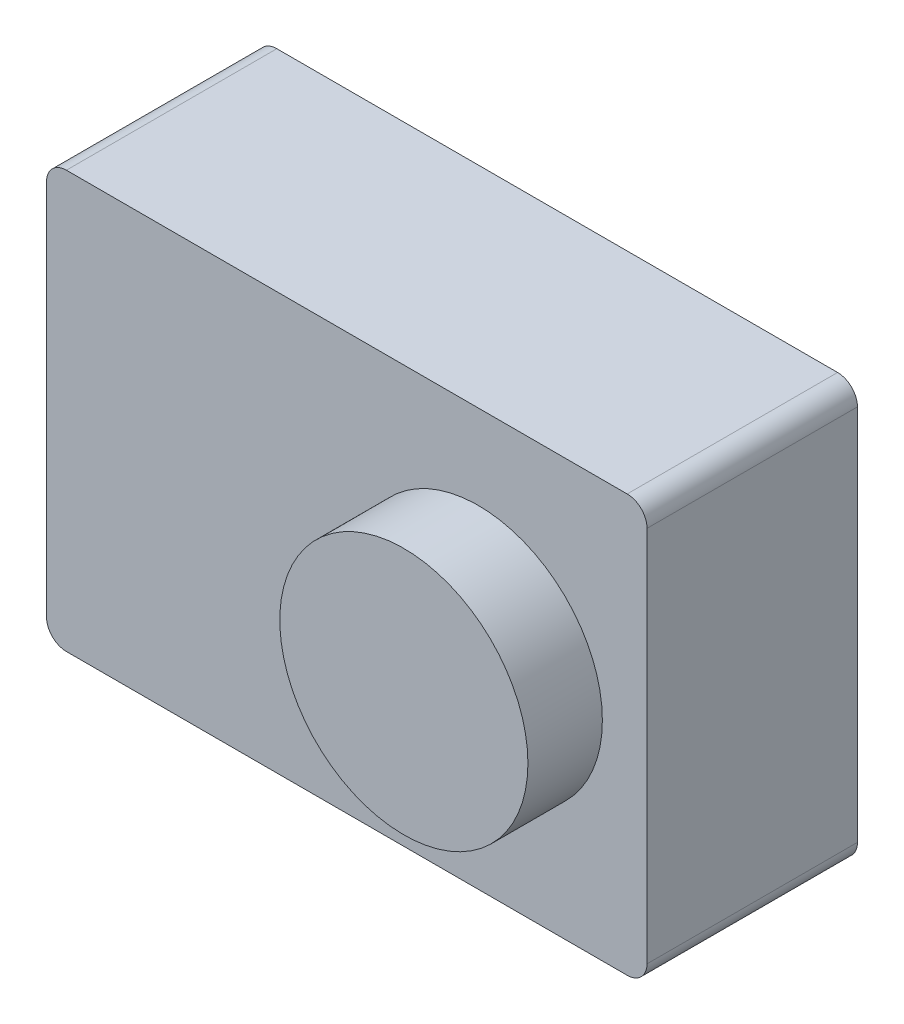
SolidWorks part; units mm, degrees
ref_plane "Front Plane" through (0, 0, 0) normal (0, 0, 1) x (1, 0, 0)
ref_plane "Top Plane" through (0, 0, 0) normal (0, 1, 0) x (1, 0, 0)
ref_plane "Right Plane" through (0, 0, 0) normal (1, 0, 0) x (0, 0, -1)
sketch "Sketch1" plane through (0, 0, 0) normal (0, 0, 1) x (1, 0, 0)
  line L1 (-28.25, -21) -> (28.25, -21)
  line L2 (-30.25, -19) -> (-30.25, 19)
  line L3 (-28.25, 21) -> (28.25, 21)
  line L4 (30.25, -19) -> (30.25, 19)
  line L5 (-30.25, -21) -> (30.25, 21) construction
  line L6 (-30.25, 21) -> (30.25, -21) construction
  arc A0 (-30.25, -19) -> (-28.25, -21) centre (-28.25, -19) ccw
  arc A1 (28.25, -21) -> (30.25, -19) centre (28.25, -19) ccw
  arc A2 (30.25, 19) -> (28.25, 21) centre (28.25, 19) ccw
  arc A3 (-28.25, 21) -> (-30.25, 19) centre (-28.25, 19) ccw
  point P0 (0, 0)
  dimension "D3" = 2
  dimension "D1" = 60.5
  dimension "D2" = 42
extrude "Boss-Extrude1" add sketch "Sketch1" along normal blind 21.2
sketch "Sketch2" plane through (0, 0, 21.2) normal (0, 0, 1) x (1, 0, 0)
  line L0 (0, 22.4408) -> (0, -22.3835) construction
  line L1 (-31.2681, 0) -> (31.6693, 0) construction
  line L2 (30.25, -19) -> (30.25, 19) construction
  circle A0 centre (13.25, 0) radius 12.5
  dimension "D2" = 25
  dimension "D1" = 17
extrude "Boss-Extrude2" add sketch "Sketch2" along normal blind 7.5
sketch "Sketch3" plane through (0, -21, 0) normal (0, -1, 0) x (1, 0, 0)
  line L0 (30.25, 21.2) -> (30.25, 0) construction
  line L1 (-28.25, 0) -> (28.25, 0) construction
  circle A0 centre (13.25, 10) radius 3
  dimension "D3" = 6
  dimension "D1" = 17
  dimension "D2" = 10
extrude "Cut-Extrude1" cut sketch "Sketch3" against normal blind 5 contours A0
